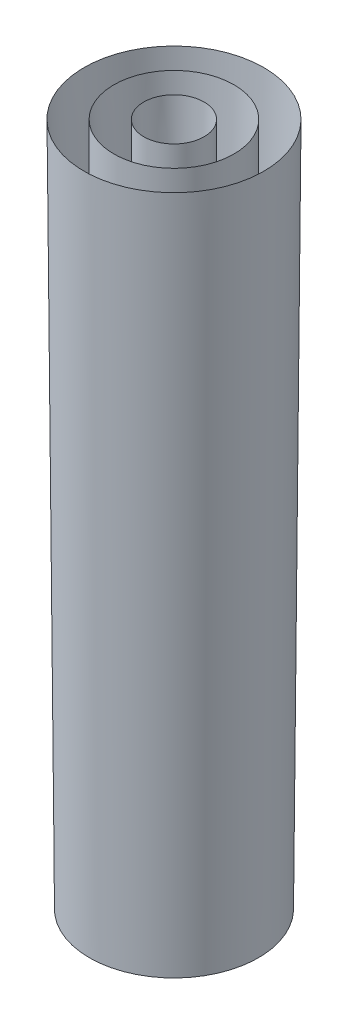
SolidWorks part; units mm, degrees
ref_plane "Спереди" through (0, 0, 0) normal (0, 0, 1) x (1, 0, 0)
ref_plane "Сверху" through (0, 0, 0) normal (0, 1, 0) x (1, 0, 0)
ref_plane "Справа" through (0, 0, 0) normal (1, 0, 0) x (0, 0, -1)
sketch "Эскиз1" plane through (0, 0, 0) normal (0, 0, 1) x (1, 0, 0)
  line L0 (29.7378, 0) -> (-2.6241, 0) construction
  line L1 (-2.6204, 150) -> (32.8417, 150) construction
  line L2 (-2.6877, -0.114) -> (-2.6877, 1.4253) construction
  line L4 (15.8598, 0) -> (16.3759, 0) construction
  line L7 (-2.6241, 0) -> (3.9258, 150)
  line L8 (3.9258, 150) -> (3.9258, 0)
  line L9 (3.9258, 0) -> (10.4758, 150)
  line L10 (10.4758, 150) -> (10.4758, 0)
  line L11 (10.4758, 0) -> (17.0257, 150)
  line L12 (17.0257, 150) -> (15.8598, 0)
  line L14 (-1.9357, 0) -> (3.2203, 109.9488)
  line L15 (3.2203, 109.9488) -> (3.5269, -1.1331)
  line L16 (3.5269, -1.1331) -> (4.2587, -1.1331)
  line L17 (4.2587, -1.1331) -> (4.6001, 6.148)
  line L18 (4.6001, 6.148) -> (9.4678, 109.9488)
  line L19 (9.4678, 109.9488) -> (10.1897, -0.8463)
  line L20 (10.1897, -0.8463) -> (10.9898, -0.8463)
  line L21 (10.9898, -0.8463) -> (11.6843, 13.9634)
  line L22 (11.6843, 13.9634) -> (15.8523, 110.4725)
  line L23 (15.8523, 110.4725) -> (15.3118, 0)
  line L25 (15.3118, 0) -> (15.8598, 0)
  line L26 (-2.6241, 0) -> (-1.9357, 0)
  line L27 (-2.6241, 0) -> (-2.6241, 1.141) construction
  dimension "D1" = 150
  dimension "D2" = 19
revolve "Повернуть1" add sketch "Эскиз1" angle 360 about L2
